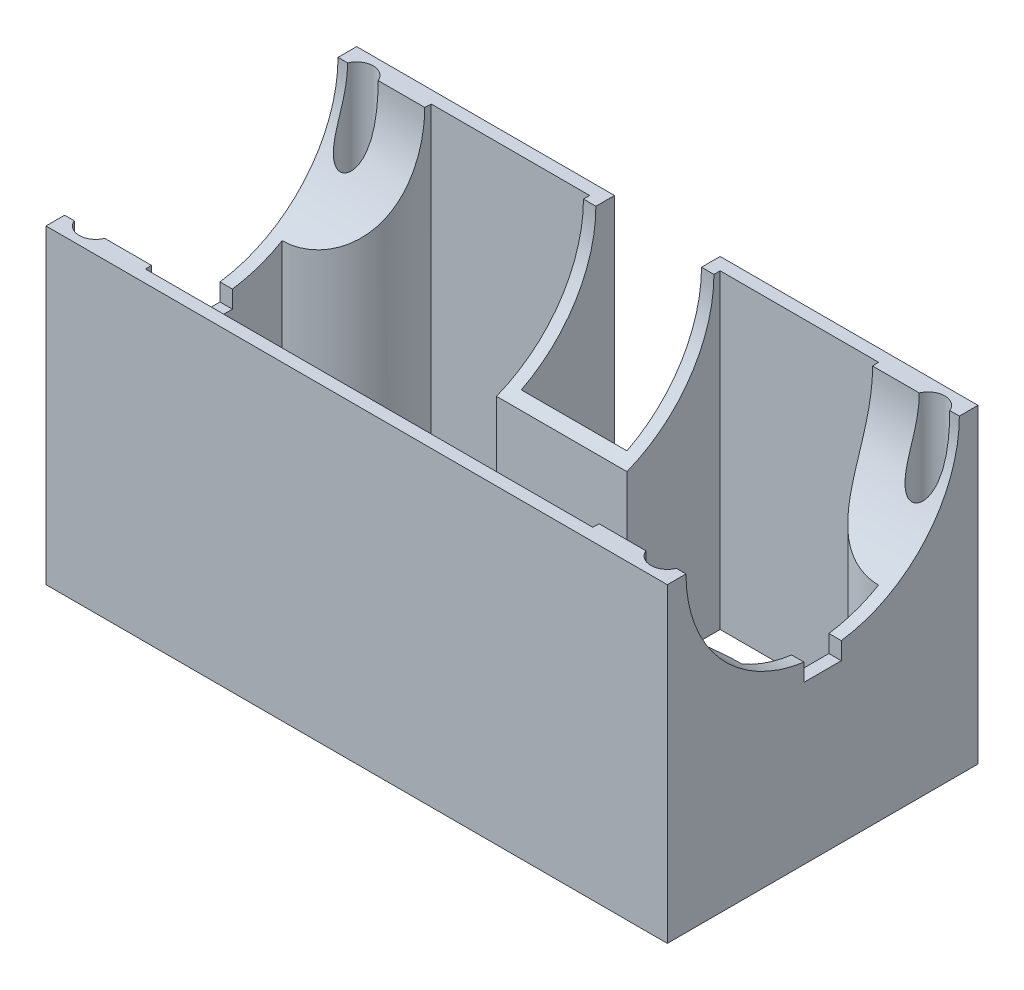
SolidWorks part; units mm, degrees
ref_plane "Front Plane" through (0, 0, 0) normal (0, 0, 1) x (1, 0, 0)
ref_plane "Top Plane" through (0, 0, 0) normal (0, 1, 0) x (1, 0, 0)
ref_plane "Right Plane" through (0, 0, 0) normal (1, 0, 0) x (0, 0, -1)
sketch "Sketch1" plane through (0, 0, 0) normal (0, 1, 0) x (1, 0, 0)
  line L0 (0, 15.5749) -> (0, 7.7994) construction
  line L1 (-25, -9.7006) -> (25, -9.7006)
  line L2 (-25, -9.7006) -> (-25, 15.2994)
  line L3 (4.25, 15.2994) -> (25, 15.2994)
  line L4 (25, -9.7006) -> (25, 15.2994)
  line L6 (-4.25, 15.2994) -> (-4.25, 7.7994)
  line L7 (-4.25, 7.7994) -> (4.25, 7.7994)
  line L8 (4.25, 15.2994) -> (4.25, 7.7994)
  line L9 (-25, 15.2994) -> (-4.25, 15.2994)
  line L11 (-5.25, 14.2994) -> (-5.25, 6.7994)
  line L12 (-5.25, 6.7994) -> (5.25, 6.7994)
  line L13 (5.25, 14.2994) -> (5.25, 6.7994)
  line L14 (5.25, 14.2994) -> (18, 14.2994)
  line L18 (-24, -8.7006) -> (-24, 14.2994) construction
  line L19 (-18, 14.2994) -> (-5.25, 14.2994)
  line L20 (-24, 14.2994) -> (-5.25, 14.2994) construction
  line L21 (-18, -8.7006) -> (18, -8.7006)
  line L22 (-24, -8.7006) -> (24, -8.7006) construction
  line L23 (-24, -2.7006) -> (-24, 8.2994)
  line L25 (24, -2.7006) -> (24, 8.2994)
  line L26 (24, -8.7006) -> (24, 14.2994) construction
  line L27 (5.25, 14.2994) -> (24, 14.2994) construction
  circle A0 centre (-23, 13.2994) radius 1.325
  circle A1 centre (23, 13.2994) radius 1.325
  circle A2 centre (23, -7.7006) radius 1.325
  circle A3 centre (-23, -7.7006) radius 1.325
  arc A4 (-24, 8.2994) -> (-18, 14.2994) centre (-24, 14.2994) ccw
  arc A5 (-18, -8.7006) -> (-24, -2.7006) centre (-24, -8.7006) ccw
  arc A6 (24, -2.7006) -> (18, -8.7006) centre (24, -8.7006) ccw
  arc A7 (18, 14.2994) -> (24, 8.2994) centre (24, 14.2994) ccw
  dimension "D6" = 2.65
  dimension "D7" = 2.65
  dimension "D8" = 2.65
  dimension "D9" = 2.65
  dimension "D19" = 12
  dimension "D20" = 12
  dimension "D21" = 12
  dimension "D22" = 12
  dimension "D1" = 50
  dimension "D2" = 25
  dimension "D3" = 7.5
  dimension "D4" = 8.5
  dimension "D5" = 25
  dimension "D10" = 2
  dimension "D11" = 2
  dimension "D12" = 2
  dimension "D13" = 2
  dimension "D14" = 2
  dimension "D15" = 2
  dimension "D16" = 2
  dimension "D17" = 2
  dimension "D18" = 1
extrude "Boss-Extrude1" add sketch "Sketch1" along normal blind 25
sketch "Sketch3" plane through (25, 0, 0) normal (1, 0, 0) x (0, 0, -1)
  line L0 (-9.7006, 25) -> (15.2994, 25) construction
  circle A0 centre (2.7994, 25) radius 11
  dimension "D1" = 22
extrude "Cut-Extrude1" cut sketch "Sketch3" against normal through all
sketch "Sketch4" plane through (25, 0, 0) normal (1, 0, 0) x (0, 0, -1)
  line L0 (15.2994, 25) -> (15.2994, 0) construction
  line L1 (1.2994, 14.2) -> (4.2994, 14.2)
  line L2 (1.2994, 14.2) -> (1.2994, 12.7)
  line L3 (1.2994, 12.7) -> (4.2994, 12.7)
  line L4 (4.2994, 14.2) -> (4.2994, 12.7)
  dimension "D1" = 3
  dimension "D2" = 1.5
  dimension "D3" = 11
  dimension "D4" = 12.7
extrude "Cut-Extrude2" cut sketch "Sketch4" against normal through all
